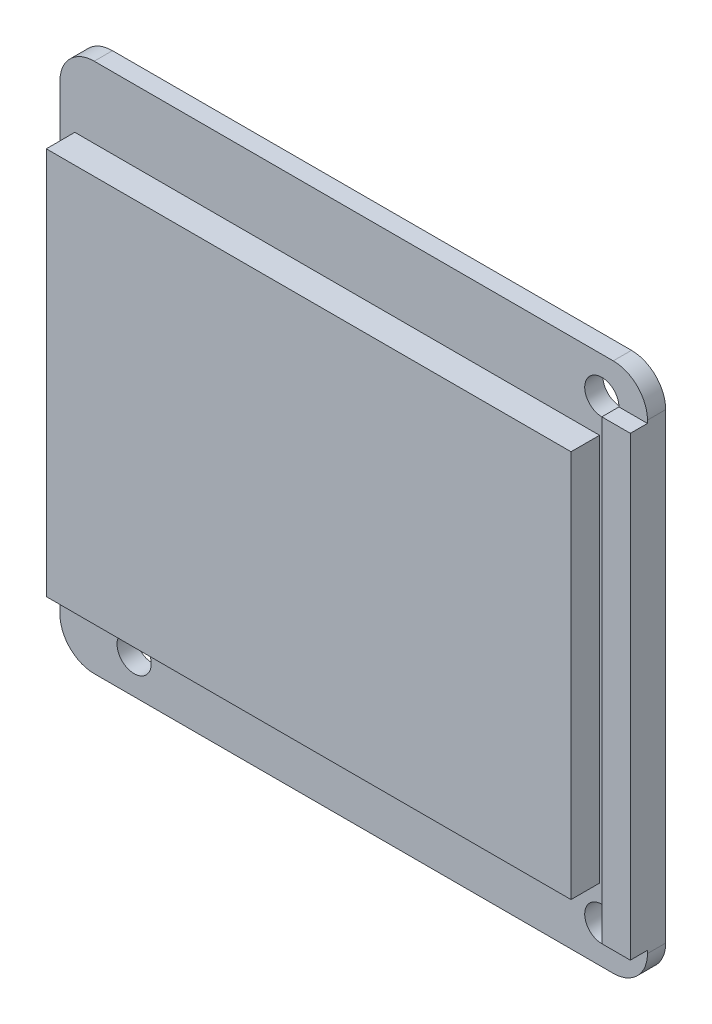
SolidWorks part; units mm, degrees
ref_plane "Front" through (0, 0, 0) normal (0, 0, 1) x (1, 0, 0)
ref_plane "Top" through (0, 0, 0) normal (0, 1, 0) x (1, 0, 0)
ref_plane "Right" through (0, 0, 0) normal (1, 0, 0) x (0, 0, -1)
sketch "Esquisse1" plane through (0, 0, 0) normal (0, 0, 1) x (1, 0, 0)
  line L1 (0, 0) -> (51.5, 0)
  line L2 (0, 0) -> (0, 46.5)
  line L3 (0, 46.5) -> (51.5, 46.5)
  line L4 (51.5, 0) -> (51.5, 46.5)
  dimension "D1" = 51.5
  dimension "D2" = 46.5
extrude "Boss.-Extru.1" add sketch "Esquisse1" along normal blind 1.6
sketch "Esquisse2" plane through (0, 0, 1.6) normal (0, 0, 1) x (1, 0, 0)
  line L1 (1.3, 40.25) -> (47.3, 40.25)
  line L2 (1.3, 40.25) -> (1.3, 6.25)
  line L3 (1.3, 6.25) -> (47.3, 6.25)
  line L4 (47.3, 40.25) -> (47.3, 6.25)
  line L5 (24.3, 40.25) -> (25.75, 46.5) construction
  line L6 (51.5, 46.5) -> (0, 46.5) construction
  line L7 (47.3, 23.25) -> (51.5, 23.25) construction
  line L8 (51.5, 0) -> (51.5, 46.5) construction
  dimension "D1" = 34
  dimension "D2" = 46
  dimension "D3" = 4.2
extrude "Boss.-Extru.2" add sketch "Esquisse2" along normal blind 2.5
sketch "Esquisse3" plane through (0, 0, 1.6) normal (0, 0, 1) x (1, 0, 0)
  line L0 (51.5, 0) -> (51.5, 46.5) construction
  line L1 (51.5, 43.25) -> (49, 43.25)
  line L2 (51.5, 43.25) -> (51.5, 3.25)
  line L3 (51.5, 3.25) -> (49, 3.25)
  line L4 (49, 43.25) -> (49, 3.25)
  line L5 (49, 23.25) -> (51.5, 23.25) construction
  dimension "D1" = 2.5
  dimension "D2" = 40
extrude "Boss.-Extru.3" add sketch "Esquisse3" along normal blind 1.5
sketch "Esquisse4" plane through (0, 0, 1.6) normal (0, 0, 1) x (1, 0, 0)
  line L0 (47.5, 3.25) -> (47.5, 43.25) construction
  line L1 (51.5, 0) -> (51.5, 3.25) construction
  line L2 (47.5, 23.25) -> (51.5, 23.25) construction
  line L3 (51.5, 3.25) -> (51.5, 43.25) construction
  line L4 (6.5, 3.25) -> (47.5, 3.25) construction
  circle A0 centre (47.5, 3.25) radius 1.5
  circle A1 centre (47.5, 43.25) radius 1.5
  circle A2 centre (6.5, 3.25) radius 1.5
  dimension "D1" = 40
  dimension "D2" = 3
  dimension "D3" = 4
  dimension "D4" = 41
extrude "Enlèv. mat.-Extru.1" cut sketch "Esquisse4" against normal through all
fillet "Congé1" radius 3 4 edges at (51.5, 46.5, 0.8) (0, 46.5, 0.8) (0, 0, 0.8) (51.5, 0, 0.8)
